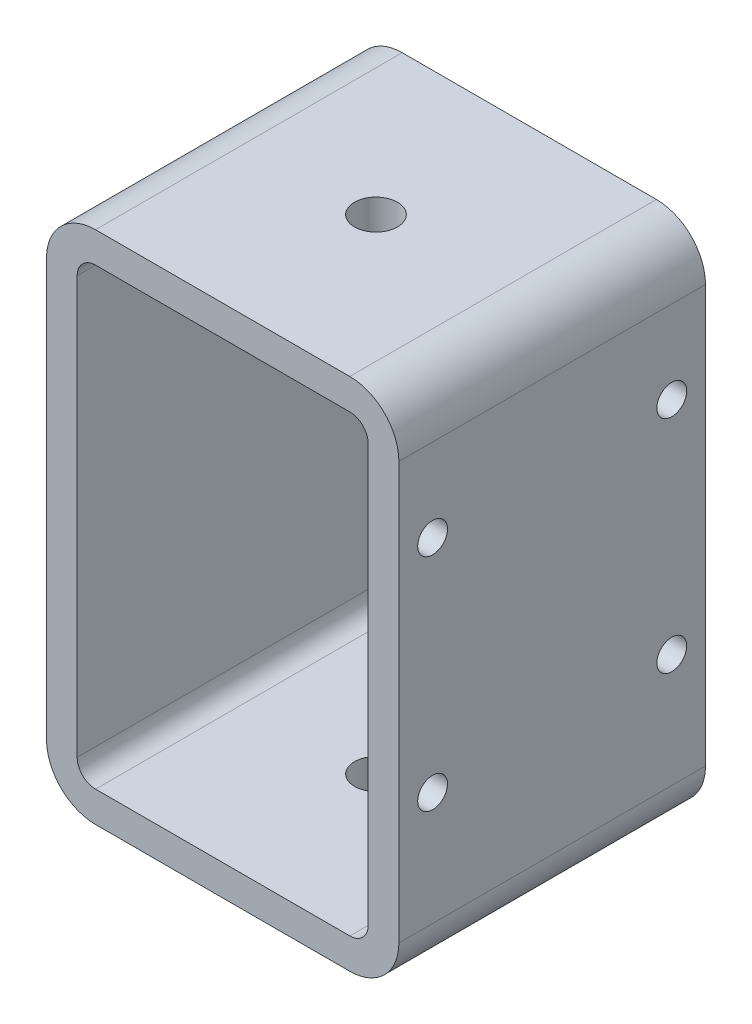
SolidWorks part; units mm, degrees
ref_plane "Front Plane" through (0, 0, 0) normal (0, 0, 1) x (1, 0, 0)
ref_plane "Top Plane" through (0, 0, 0) normal (0, 1, 0) x (1, 0, 0)
ref_plane "Right Plane" through (0, 0, 0) normal (1, 0, 0) x (0, 0, -1)
sketch "Sketch1" plane through (0, 0, 0) normal (0, 0, 1) x (1, 0, 0)
  line L0 (0, 4) -> (0, 38)
  line L1 (4, 42) -> (24.73, 42)
  line L2 (28.73, 38) -> (28.73, 4)
  line L3 (24.73, 0) -> (4, 0)
  arc A0 (4, 0) -> (0, 4) centre (4, 4) cw
  arc A1 (24.73, 0) -> (28.73, 4) centre (24.73, 4) ccw
  arc A2 (28.73, 38) -> (24.73, 42) centre (24.73, 38) ccw
  arc A3 (4, 42) -> (0, 38) centre (4, 38) ccw
  point P11 (0, 0)
  point P16 (28.73, 42)
  point P19 (0, 42)
  dimension "D3" = 4
  dimension "D1" = 42
  dimension "D2" = 28.73
extrude "Boss-Extrude1" add sketch "Sketch1" along normal blind 25
shell "Shell1" thickness 2.5
sketch "Sketch2" plane through (0, 42, 0) normal (0, 1, 0) x (1, 0, 0)
  line L0 (14.365, 0) -> (14.365, -25) construction
  line L1 (24.73, 0) -> (4, 0) construction
  line L2 (24.73, -25) -> (4, -25) construction
  line L3 (0, -12.5) -> (28.73, -12.5) construction
  line L4 (0, -25) -> (0, 0) construction
  line L5 (28.73, -25) -> (28.73, 0) construction
  circle A0 centre (14.365, -12.5) radius 1.75
  dimension "D1" = 3.5
extrude "Cut-Extrude1" cut sketch "Sketch2" against normal through all
sketch "Sketch3" plane through (28.73, 0, 0) normal (1, 0, 0) x (0, 0, -1)
  line L0 (-25, 4) -> (-25, 38) construction
  line L1 (-25, 42) -> (0, 42) construction
  circle A0 centre (-22.25, 31.25) radius 1.215
  dimension "D1" = 2.43
  dimension "D2" = 2.75
  dimension "D3" = 10.75
extrude "Cut-Extrude2" cut sketch "Sketch3" against normal up to surface (2.5 mm away) up to face at (26.23, 21, 12.5)
pattern_linear "LPattern1" count 2 spacing 18 along (0, -1, 0) count 2 spacing 19.5 along (0, 0, -1) of "Cut-Extrude2"
